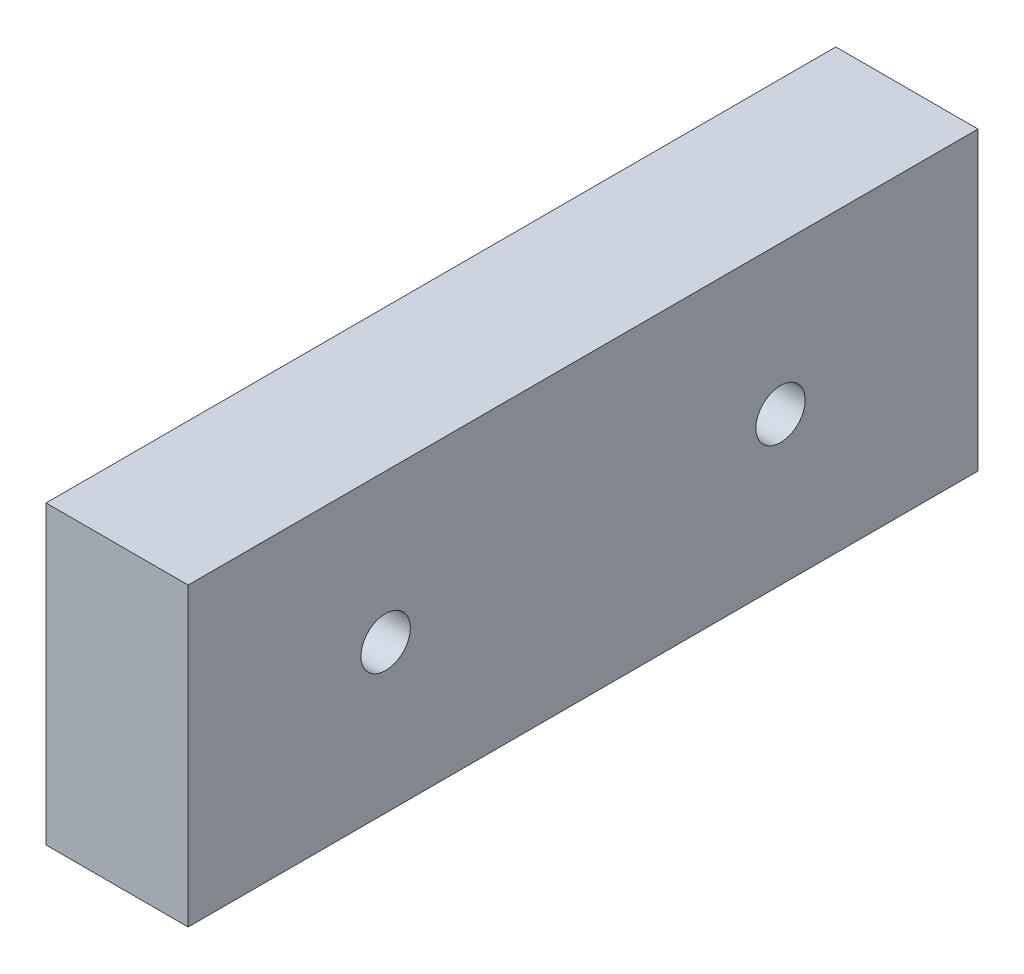
SolidWorks part; units mm, degrees
ref_plane "Front" through (0, 0, 0) normal (0, 0, 1) x (1, 0, 0)
ref_plane "Top" through (0, 0, 0) normal (0, 1, 0) x (1, 0, 0)
ref_plane "Right" through (0, 0, 0) normal (1, 0, 0) x (0, 0, -1)
sketch "Sketch1" plane through (0, 0, 0) normal (1, 0, 0) x (0, 0, -1)
  line L1 (50.8, -19.05) -> (-50.8, -19.05)
  line L2 (50.8, -19.05) -> (50.8, 19.05)
  line L3 (50.8, 19.05) -> (-50.8, 19.05)
  line L4 (-50.8, -19.05) -> (-50.8, 19.05)
  line L5 (50.8, -19.05) -> (-50.8, 19.05) construction
  line L6 (50.8, 19.05) -> (-50.8, -19.05) construction
  circle A0 centre (-25.4, 0) radius 3.175
  circle A1 centre (25.4, 0) radius 3.175
  point P0 (0, 0)
  dimension "D3" = 6.35
  dimension "D4" = 6.35
  dimension "D6" = 25.4
  dimension "D1" = 38.1
  dimension "D2" = 101.6
  dimension "D5" = 25.4
extrude "Boss-Extrude1" add sketch "Sketch1" along normal blind 18.288
